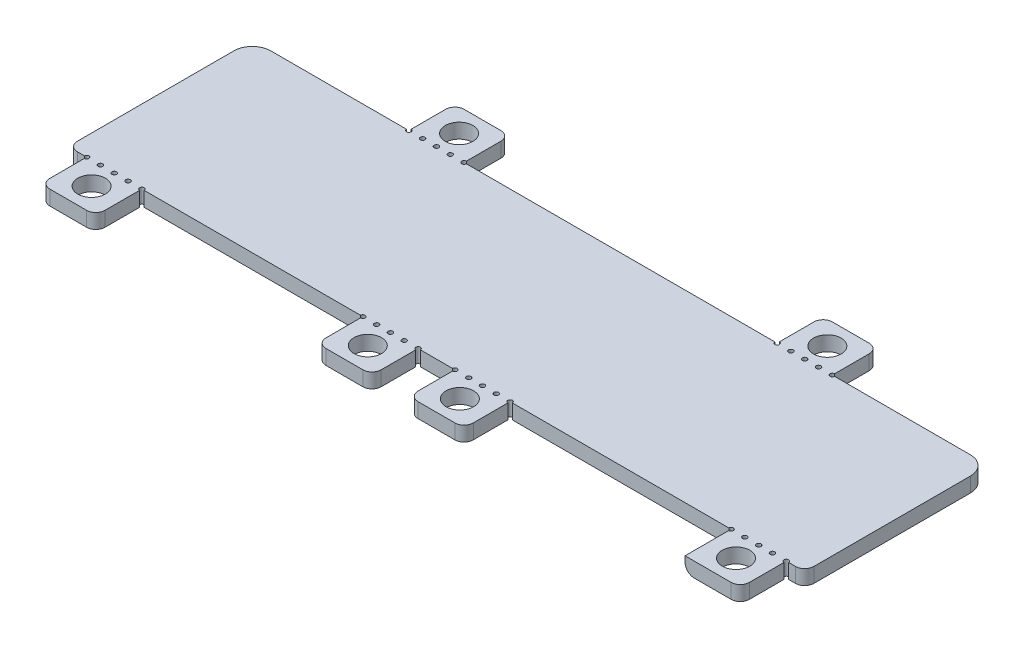
SolidWorks part; units mm, degrees
material "Титан Ti-8Al-1Mo-1V"
ref_plane "Спереди" through (0, 0, 0) normal (0, 0, 1) x (1, 0, 0)
ref_plane "Сверху" through (0, 0, 0) normal (0, 1, 0) x (1, 0, 0)
ref_plane "Справа" through (0, 0, 0) normal (1, 0, 0) x (0, 0, -1)
sketch "Эскиз1" plane through (0, 0, 0) normal (0, 1, 0) x (1, 0, 0)
  line L0 (0, 20.4814) -> (0, -12.6039) construction
  line L1 (40, -10) -> (-40, -10)
  line L2 (40, -10) -> (40, 10)
  line L3 (40, 10) -> (-40, 10)
  line L4 (-40, -10) -> (-40, 10)
  line L5 (40, -10) -> (-40, 10) construction
  line L6 (40, 10) -> (-40, -10) construction
  line L7 (8, -15) -> (2, -15)
  line L8 (-23, 10) -> (-17, 10)
  line L9 (-23, 10) -> (-23, 15)
  line L10 (-23, 15) -> (-17, 15)
  line L11 (-17, 10) -> (-17, 15)
  line L12 (-38, -10) -> (-32, -10)
  line L13 (-38, -10) -> (-38, -15)
  line L14 (-38, -15) -> (-32, -15)
  line L15 (-32, -10) -> (-32, -15)
  line L16 (-8, -10) -> (-2, -10)
  line L17 (-8, -10) -> (-8, -15)
  line L18 (-8, -15) -> (-2, -15)
  line L19 (-2, -10) -> (-2, -15)
  line L20 (2, -10) -> (2, -15)
  line L21 (8, -10) -> (2, -10)
  line L22 (8, -10) -> (8, -15)
  line L23 (23, 15) -> (17, 15)
  line L24 (17, 10) -> (17, 15)
  line L25 (23, 10) -> (17, 10)
  line L26 (23, 10) -> (23, 15)
  line L27 (38, -15) -> (32, -15)
  line L28 (32, -10) -> (32, -15)
  line L29 (38, -10) -> (32, -10)
  line L30 (38, -10) -> (38, -15)
  point P0 (0, 0)
  dimension "D1" = 80
  dimension "D2" = 20
  dimension "D3" = 6
  dimension "D4" = 5
  dimension "D5" = 34
  dimension "D6" = 5
  dimension "D7" = 6
  dimension "D8" = 6
  dimension "D9" = 5
  dimension "D10" = 16
  dimension "D11" = 76
extrude "Бобышка-Вытянуть1" add sketch "Эскиз1" along normal blind 1.6 contours L3 L11 L10 L9 | L4 L1 L2 L3 | L3 L26 L23 L24 | L30 L1 L28 L27 | L22 L1 L20 L7 | L19 L1 L17 L18 | L15 L1 L13 L14
sketch "Эскиз2" plane through (0, 1.6, 0) normal (0, 1, 0) x (1, 0, 0)
  line L0 (0, 17.7838) -> (0, -18.0297) construction
  line L1 (-23, 15) -> (-17, 15) construction
  line L2 (-38, -15) -> (-32, -15) construction
  line L3 (-8, -15) -> (-2, -15) construction
  line L4 (-23, 10) -> (-23, 15) construction
  line L6 (-38, -10) -> (-38, -15) construction
  line L7 (-8, -10) -> (-8, -15) construction
  circle A0 centre (-20, 12.46) radius 1.5
  circle A1 centre (-35, -12.46) radius 1.5
  circle A2 centre (-5, -12.46) radius 1.5
  circle A3 centre (5, -12.46) radius 1.5
  circle A4 centre (35, -12.46) radius 1.5
  circle A5 centre (20, 12.46) radius 1.5
  dimension "D1" = 3
  dimension "D2" = 2.54
  dimension "D3" = 2.54
  dimension "D4" = 2.54
  dimension "D5" = 3
  dimension "D6" = 3
  dimension "D7" = 3
extrude "Вырез-Вытянуть1" cut sketch "Эскиз2" against normal through all
fillet "Скругление1" radius 1 14 edges at (-23, 0.8, -15) (-17, 0.8, -15) (17, 0.8, -15) (23, 0.8, -15) (38, 0.8, 15) (32, 0, 12.5) (8, 0.8, 15) (2, 0.8, 15) (-2, 0.8, 15) (-8, 0.8, 15) (-32, 0.8, 15) (-38, 0.8, 15) (40, 0.8, 10) (-40, 0.8, 10)
sketch "Эскиз3" plane through (0, 1.6, 0) normal (0, 1, 0) x (1, 0, 0)
  line L0 (-23, 10) -> (-17, 10) construction
  line L1 (-38, -10) -> (-32, -10) construction
  line L2 (-8, -10) -> (-2, -10) construction
  line L3 (0, -10) -> (0, 10) construction
  line L4 (2, -10) -> (-2, -10) construction
  line L5 (17, 10) -> (-17, 10) construction
  circle A1 centre (-23, 10) radius 0.25
  circle A2 centre (-21.5, 10) radius 0.25
  circle A3 centre (-20, 10) radius 0.25
  circle A4 centre (-18.5, 10) radius 0.25
  circle A5 centre (-17, 10) radius 0.25
  circle A6 centre (-38, -10) radius 0.25
  circle A7 centre (-36.5, -10) radius 0.25
  circle A8 centre (-35, -10) radius 0.25
  circle A9 centre (-33.5, -10) radius 0.25
  circle A10 centre (-32, -10) radius 0.25
  circle A11 centre (-8, -10) radius 0.25
  circle A12 centre (-6.5, -10) radius 0.25
  circle A13 centre (-5, -10) radius 0.25
  circle A14 centre (-3.5, -10) radius 0.25
  circle A15 centre (-2, -10) radius 0.25
  circle A16 centre (2, -10) radius 0.25
  circle A17 centre (3.5, -10) radius 0.25
  circle A18 centre (5, -10) radius 0.25
  circle A19 centre (6.5, -10) radius 0.25
  circle A20 centre (8, -10) radius 0.25
  circle A21 centre (32, -10) radius 0.25
  circle A22 centre (33.5, -10) radius 0.25
  circle A23 centre (35, -10) radius 0.25
  circle A24 centre (36.5, -10) radius 0.25
  circle A25 centre (38, -10) radius 0.25
  circle A26 centre (17, 10) radius 0.25
  circle A27 centre (18.5, 10) radius 0.25
  circle A28 centre (20, 10) radius 0.25
  circle A29 centre (21.5, 10) radius 0.25
  circle A30 centre (23, 10) radius 0.25
  dimension "D1" = 0.5
  dimension "D2" = 5
  dimension "D3" = 5
  dimension "D4" = 5
extrude "Вырез-Вытянуть2" cut sketch "Эскиз3" against normal through all
fillet "Скругление2" radius 2 2 edges at (40, 0.8, -10) (-40, 0.8, -10)
equation "\"D6@Эскиз1\"=\"D4@Эскиз1\""
equation "\"D7@Эскиз1\"=\"D3@Эскиз1\""
equation "\"D8@Эскиз1\"=\"D3@Эскиз1\""
equation "\"D9@Эскиз1\"=\"D4@Эскиз1\""
equation "\"D3@Эскиз2\"=\"D2@Эскиз2\""
equation "\"D4@Эскиз2\"=\"D2@Эскиз2\""
equation "\"D6@Эскиз2\"=\"D5@Эскиз2\""
equation "\"D7@Эскиз2\"=\"D5@Эскиз2\""
